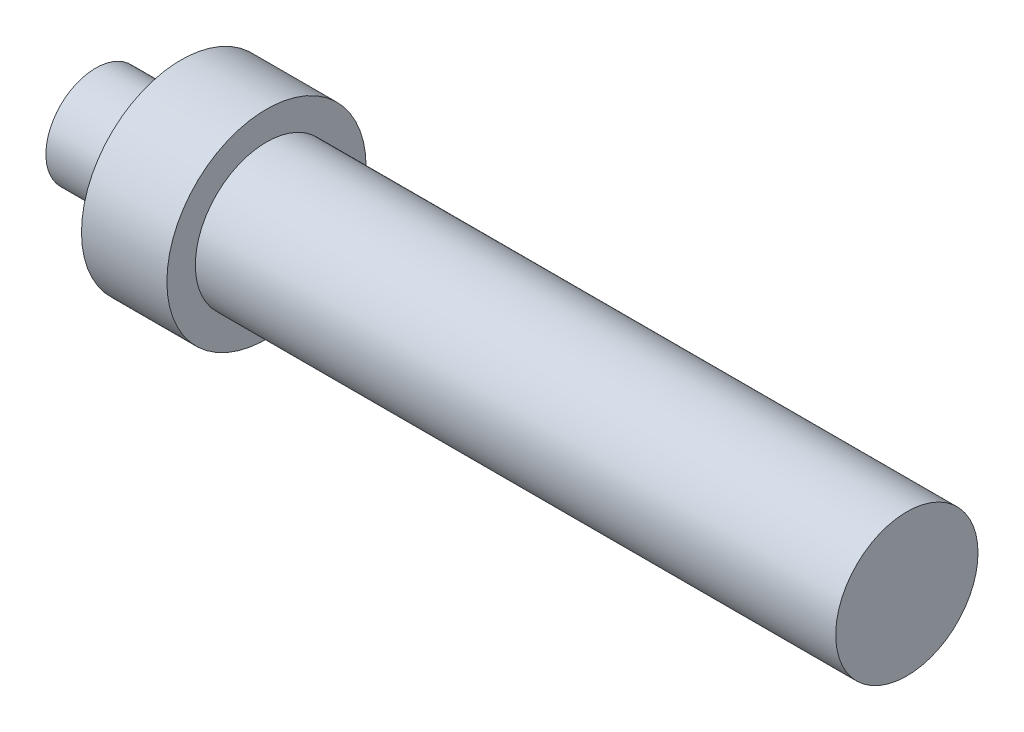
SolidWorks part; units mm, degrees
ref_plane "Front Plane" through (0, 0, 0) normal (0, 0, 1) x (1, 0, 0)
ref_plane "Top Plane" through (0, 0, 0) normal (0, 1, 0) x (1, 0, 0)
ref_plane "Right Plane" through (0, 0, 0) normal (1, 0, 0) x (0, 0, -1)
sketch "Sketch1" plane through (0, 0, 0) normal (0, 0, 1) x (1, 0, 0)
  line L0 (28.5, 0) -> (-28.5, 0)
  line L1 (-28.5, 0) -> (-28.5, 3.5)
  line L2 (-28.5, 3.5) -> (-22.5, 3.5)
  line L3 (28.5, 0) -> (28.5, 5)
  line L4 (28.5, 5) -> (-16.5, 5)
  line L5 (-16.5, 5) -> (-16.5, 7)
  line L6 (-16.5, 7) -> (-22.5, 7)
  line L7 (-22.5, 7) -> (-22.5, 3.5)
  point P4 (0, 0)
revolve "Revolve1" add sketch "Sketch1" angle 360 about L0
